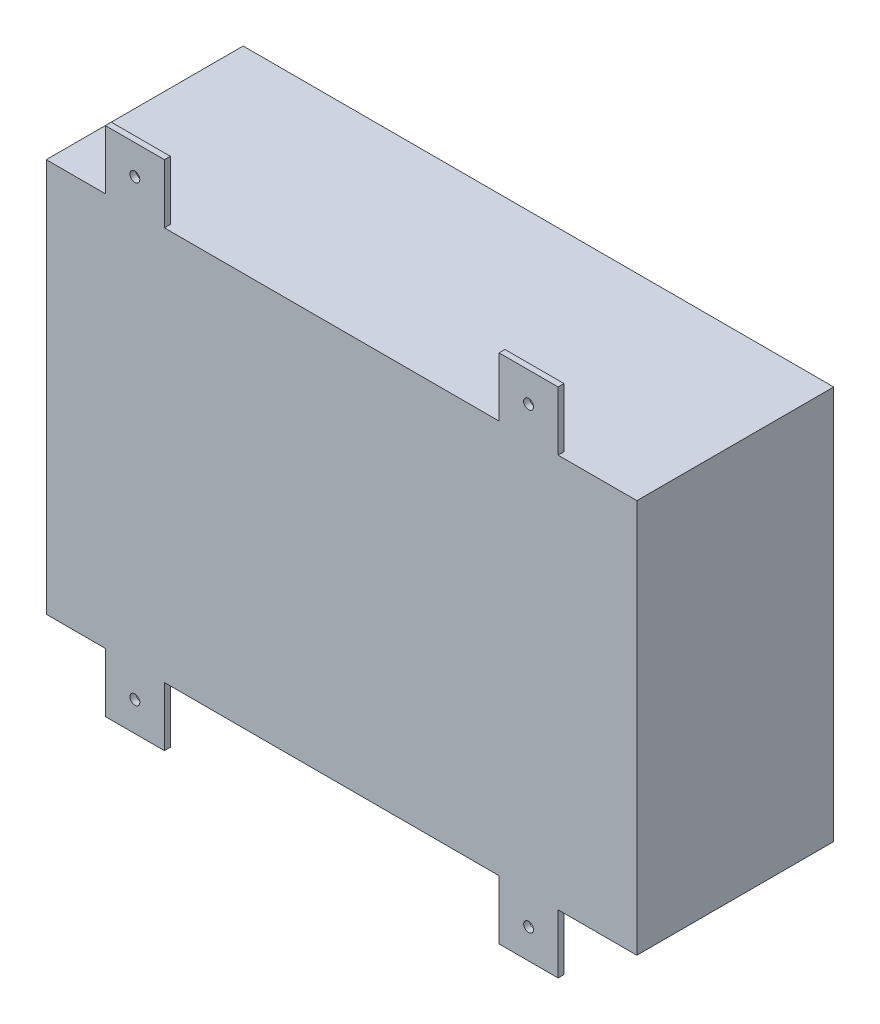
SolidWorks part; units mm, degrees
material "Custom Plastic"
ref_plane "Front Plane" through (0, 0, 0) normal (0, 0, 1) x (1, 0, 0)
ref_plane "Top Plane" through (0, 0, 0) normal (0, 1, 0) x (1, 0, 0)
ref_plane "Right Plane" through (0, 0, 0) normal (1, 0, 0) x (0, 0, -1)
sketch "Sketch1" plane through (0, 0, 0) normal (0, 0, 1) x (1, 0, 0)
  line L0 (-355.6, 228.6) -> (355.6, 228.6)
  line L1 (-381, -254) -> (381, -254)
  line L2 (-381, -254) -> (-381, 254)
  line L3 (-381, 254) -> (381, 254)
  line L4 (381, -254) -> (381, 254)
  line L5 (-381, -254) -> (381, 254) construction
  line L6 (-381, 254) -> (381, -254) construction
  line L7 (355.6, -228.6) -> (355.6, 228.6)
  line L8 (-355.6, -228.6) -> (355.6, -228.6)
  line L9 (-355.6, -228.6) -> (-355.6, 228.6)
  point P0 (0, 0)
  dimension "D1" = 508
  dimension "D2" = 762
  dimension "D3" = 25.4
extrude "Boss-Extrude1" add sketch "Sketch1" along normal blind 254
sketch "Sketch2" plane through (0, 0, 254) normal (0, 0, 1) x (1, 0, 0)
  line L1 (-355.6, -228.6) -> (355.6, -228.6)
  line L2 (-355.6, -228.6) -> (-355.6, 228.6)
  line L3 (-355.6, 228.6) -> (355.6, 228.6)
  line L4 (355.6, -228.6) -> (355.6, 228.6)
  line L5 (-355.6, -228.6) -> (355.6, 228.6) construction
  line L6 (-355.6, 228.6) -> (355.6, -228.6) construction
  point P0 (0, 0)
extrude "Boss-Extrude2" add sketch "Sketch2" against normal blind 25.4
sketch "Sketch3" plane through (0, 0, 254) normal (0, 0, 1) x (1, 0, 0)
  line L0 (-304.8, -330.2) -> (-304.8, -254)
  line L1 (-304.8, 254) -> (-228.6, 254)
  line L2 (-304.8, 254) -> (-304.8, 330.2)
  line L3 (-304.8, 330.2) -> (-228.6, 330.2)
  line L4 (-228.6, 254) -> (-228.6, 330.2)
  line L5 (-304.8, -254) -> (-228.6, -254)
  line L6 (-228.6, -330.2) -> (-228.6, -254)
  line L7 (-304.8, -330.2) -> (-228.6, -330.2)
  line L8 (203.2, -330.2) -> (203.2, -254)
  line L9 (381, -254) -> (381, 254) construction
  line L10 (381, 254) -> (-381, 254) construction
  line L11 (203.2, -254) -> (279.4, -254)
  line L12 (279.4, -330.2) -> (279.4, -254)
  line L13 (203.2, -330.2) -> (279.4, -330.2)
  line L14 (203.2, 254) -> (203.2, 330.2)
  line L15 (203.2, 330.2) -> (279.4, 330.2)
  line L16 (279.4, 254) -> (279.4, 330.2)
  line L17 (203.2, 254) -> (279.4, 254)
  circle A0 centre (-266.7, -292.1) radius 6.35
  circle A1 centre (-266.7, 292.1) radius 6.35
  circle A2 centre (241.3, 292.1) radius 6.35
  circle A3 centre (241.3, -292.1) radius 6.35
  dimension "D2" = 2
  dimension "D3" = 101.6
  dimension "D8" = 12.7
  dimension "D9" = 139.7
  dimension "D1" = 2
  dimension "D4" = 177.8
  dimension "D5" = 609.6
  dimension "D6" = 76.2
  dimension "D7" = 508
  dimension "D10" = 647.7
  dimension "D11" = 38.1
  dimension "D12" = 546.1
extrude "Boss-Extrude3" add sketch "Sketch3" against normal blind 7.62
sketch "Sketch4" plane through (0, -254, 0) normal (0, -1, 0) x (1, 0, 0)
  line L0 (-304.8, 246.38) -> (-304.8, 254) construction
  line L1 (-228.6, 246.38) -> (-304.8, 246.38) construction
  circle A0 centre (0, 127) radius 63.5
  dimension "D1" = 127
  dimension "D2" = 304.8
  dimension "D3" = 119.38
extrude "Cut-Extrude1" cut sketch "Sketch4" against normal blind 133.096
scale "Scale1" bodies to scale 104 scale about origin uniform scaling yes scale factor 0.5
